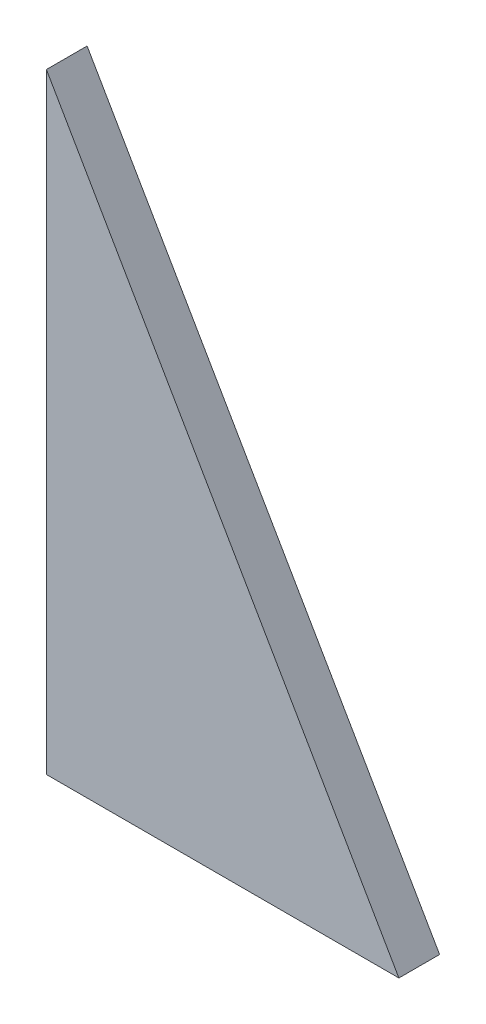
SolidWorks part; units mm, degrees
ref_plane "Alzado" through (0, 0, 0) normal (0, 0, 1) x (1, 0, 0)
ref_plane "Planta" through (0, 0, 0) normal (0, 1, 0) x (1, 0, 0)
ref_plane "Vista lateral" through (0, 0, 0) normal (1, 0, 0) x (0, 0, -1)
sketch "Croquis1" plane through (0, 0, 0) normal (0, 0, 1) x (1, 0, 0)
  line L0 (0, 0) -> (-8.6603, 15)
  line L1 (-8.6603, 15) -> (-8.6603, 0)
  line L2 (-8.6603, 0) -> (-2.2061, 0)
  line L3 (-2.2061, 0) -> (0, 0)
  dimension "D1" = 60
  dimension "D2" = 15
extrude "Saliente-Extruir1" add sketch "Croquis1" along normal blind 1
